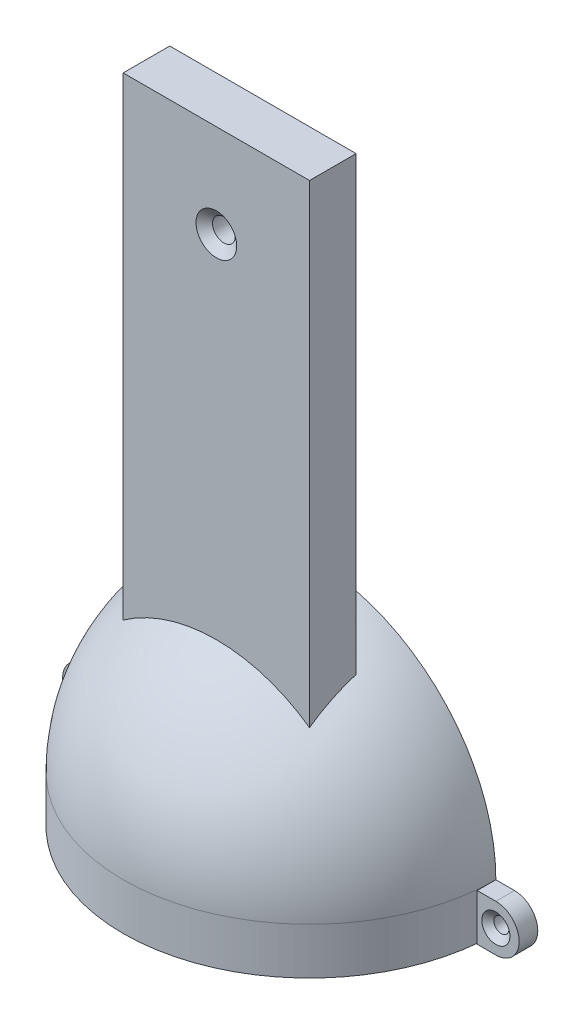
SolidWorks part; units mm, degrees
ref_plane "Front Plane" through (0, 0, 0) normal (0, 0, 1) x (1, 0, 0)
ref_plane "Top Plane" through (0, 0, 0) normal (0, 1, 0) x (1, 0, 0)
ref_plane "Right Plane" through (0, 0, 0) normal (1, 0, 0) x (0, 0, -1)
sketch "Sketch1" plane through (0, 0, 0) normal (0, 0, 1) x (1, 0, 0)
  line L0 (-15, 0) -> (-10, 0)
  line L2 (-20, 0) -> (-20, -10)
  line L3 (-20, -10) -> (-10, -10)
  line L4 (20, 0) -> (20, -10)
  line L6 (-10, -10) -> (-10, 0)
  line L8 (10, -10) -> (10, 0)
  line L9 (10, 0) -> (15, 0)
  line L10 (10, -10) -> (20, -10)
  line L11 (-20, 0) -> (20, 0)
  arc A0 (20, 0) -> (-20, 0) centre (0, 0) ccw
  arc A3 (15, 0) -> (-15, 0) centre (0, 0) ccw
  dimension "D1" = 10
  dimension "D2" = 20
  dimension "D4" = 10
  dimension "D6" = 15
  dimension "D3" = 10
  dimension "D5" = 10
revolve "Revolve2" add sketch "Sketch1" angle 90 about L9
sketch "Sketch3" plane through (0, 0, 0) normal (0, -1, 0) x (1, 0, 0)
  line L0 (-15, 0) -> (15, 0) construction
  line L1 (-20, 0) -> (-10, 0)
  line L2 (10, 0) -> (20, 0)
  arc A0 (10, 0) -> (-10, 0) centre (0, 0) ccw
  arc A1 (20, 0) -> (-20, 0) centre (0, 0) ccw
  dimension "D1" = 10
extrude "Boss-Extrude2" add sketch "Sketch3" along normal blind 5
sketch "Sketch5" plane through (0, 0, 0) normal (0, 0, -1) x (-1, 0, 0)
  line L2 (0, 11) -> (0, -11) construction
  line L3 (-22, 0) -> (-20, 0)
  line L5 (-22, -5) -> (-20, -5)
  line L6 (-20, 0) -> (-20, -5)
  line L7 (22, -5) -> (20, -5)
  line L8 (22, 0) -> (20, 0)
  line L9 (20, -5) -> (20, 0)
  arc A0 (-22, 0) -> (-22, -5) centre (-22, -2.5) ccw
  arc A1 (22, 0) -> (22, -5) centre (22, -2.5) cw
  dimension "D1" = 2.5
extrude "Boss-Extrude3" add sketch "Sketch5" against normal blind 2 separate body
hole_wizard "CSK for #0 Flat Head Machine Screw (100)3" positions "3DSketch5" profile "Sketch9" countersink size "#0" standard "ANSI Inch" end condition through all
sketch3d "3DSketch5"
  line L0 (22, -2.5, 2) -> (22, -2.5, 0) construction
  point P0 (22, -2.5, 2)
  point P5 (-22, -2.5, 2)
sketch "Sketch9" plane through (22, -2.5, 2) normal (1, 0, 0) x (0, -1, 0)
  line L0 (0, 0) -> (0, 2)
  line L1 (0, 2) -> (0.8064, 2)
  line L2 (0.8064, 2) -> (0.8064, 0.5914)
  line L3 (0.8064, 0.5914) -> (1.5113, 0)
  line L5 (1.5113, 0) -> (0, 0)
  line L6 (-0.8064, 0.5914) -> (-1.5113, 0) construction
  line L11 (0, -6.35) -> (0, 107.95) construction
  dimension "Thru Hole Dia." = 1.6129
  dimension "Thru Hole Depth" = 2
  dimension "Near C'Sink Dia." = 3.0226
  dimension "Near C'Sink Angle" = 100
sketch "Sketch10" plane through (0, 0, 0) normal (0, 1, 0) x (1, 0, 0)
  line L0 (10, 0) -> (15, 0) construction
  line L1 (10, -5) -> (-10, -5)
  line L2 (10, -5) -> (10, -10)
  line L3 (10, -10) -> (-10, -10)
  line L4 (-10, -5) -> (-10, -10)
  dimension "D1" = 20
  dimension "D2" = 5
  dimension "D3" = 5
  dimension "D4" = 10
extrude "Boss-Extrude4" add sketch "Sketch10" along normal blind 50 and the other way up to body from offset 15 separate body
sketch "Sketch11" plane through (0, 0, 5) normal (0, 0, -1) x (-1, 0, 0)
  line L0 (-10, 65) -> (10, 65) construction
  circle A0 centre (0, 55) radius 5
  dimension "D1" = 10
  dimension "D2" = 10
extrude "Boss-Extrude6" add sketch "Sketch11" along normal blind 5
hole_wizard "CSK for #2 Flat Head Machine Screw (100)1" positions "3DSketch9" profile "Sketch15" countersink size "#2" standard "ANSI Inch" end condition through all
sketch3d "3DSketch9"
  circle A0 centre (0, 55, 5) radius 5 construction
  point P0 (0, 55, 10)
  point P6 (0, 55, 0)
sketch "Sketch15" plane through (0, 55, 10) normal (1, 0, 0) x (0, -1, 0)
  line L0 (0, 0) -> (0, 10)
  line L1 (0, 10) -> (1.2192, 10)
  line L2 (1.2192, 10) -> (1.2192, 0.8099)
  line L3 (1.2192, 0.8099) -> (2.1844, 0)
  line L5 (2.1844, 0) -> (0, 0)
  line L6 (-1.2192, 0.8099) -> (-2.1844, 0) construction
  line L11 (0, -6.35) -> (0, 107.95) construction
  dimension "Thru Hole Dia." = 2.4384
  dimension "Thru Hole Depth" = 10
  dimension "Near C'Sink Dia." = 4.3688
  dimension "Near C'Sink Angle" = 100
